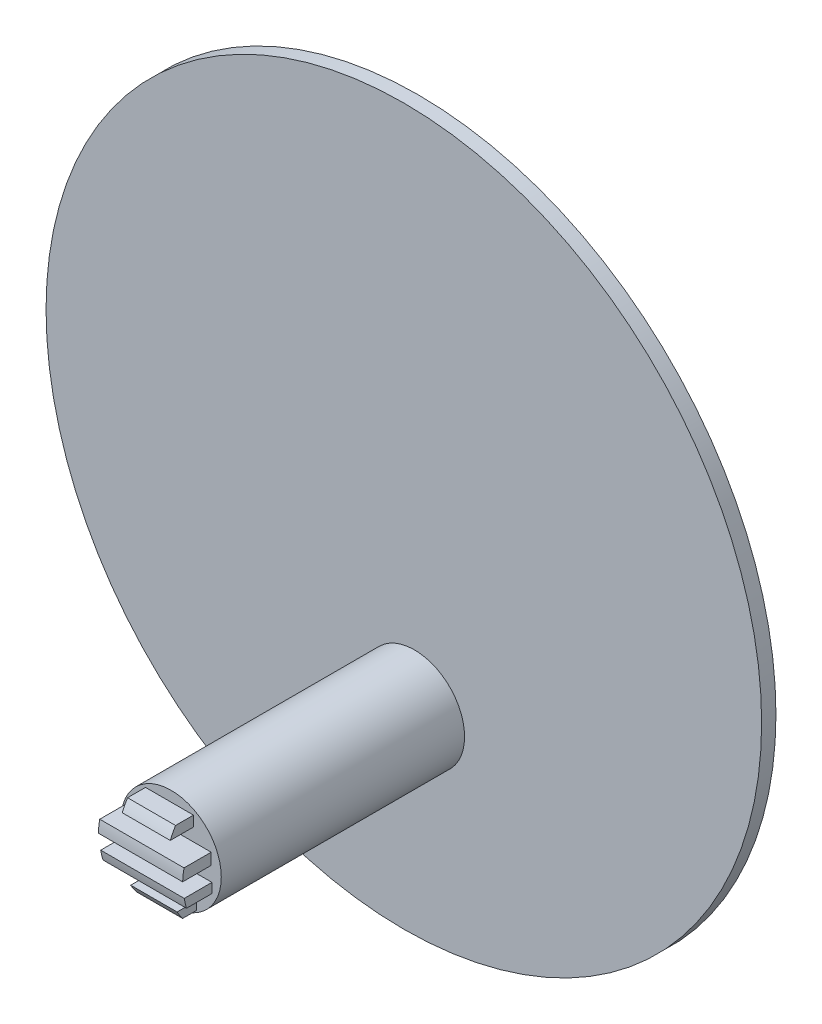
SolidWorks part; units mm, degrees
ref_plane "Front Plane" through (0, 0, 0) normal (0, 0, 1) x (1, 0, 0)
ref_plane "Top Plane" through (0, 0, 0) normal (0, 1, 0) x (1, 0, 0)
ref_plane "Right Plane" through (0, 0, 0) normal (1, 0, 0) x (0, 0, -1)
sketch "Sketch1" plane through (0, 0, 0) normal (0, 0, 1) x (1, 0, 0)
  circle A0 centre (-6.1844, 0) radius 10
  dimension "D1" = 20
extrude "Boss-Extrude1" add sketch "Sketch1" along normal blind 0.4
sketch "Sketch2" plane through (0, 0, 0.4) normal (0, 0, 1) x (1, 0, 0)
  circle A0 centre (-5.8869, -4.4881) radius 1.4
  dimension "D1" = 2.8
extrude "Boss-Extrude2" add sketch "Sketch2" along normal blind 6.8
sketch "Sketch5" plane through (0, 0, 7.2) normal (0, 0, 1) x (1, 0, 0)
  line L1 (-6.474, -5.6393) -> (-5.1772, -5.6393)
  line L2 (-6.474, -5.6393) -> (-6.474, -5.405)
  line L3 (-6.474, -5.405) -> (-5.1772, -5.405)
  line L4 (-5.1772, -5.6393) -> (-5.1772, -5.405)
extrude "Boss-Extrude4" add sketch "Sketch5" along normal up to surface (0.3908 mm away) separate body
sketch "Sketch6" plane through (0, 0, 7.2) normal (0, 0, 1) x (1, 0, 0)
  line L1 (-7.0819, -5.0165) -> (-4.7474, -5.0165)
  line L2 (-7.0819, -5.0165) -> (-7.0819, -4.7462)
  line L3 (-7.0819, -4.7462) -> (-4.7474, -4.7462)
  line L4 (-4.7474, -5.0165) -> (-4.7474, -4.7462)
extrude "Boss-Extrude5" add sketch "Sketch6" along normal up to surface (0.7112 mm away)
sketch "Sketch7" plane through (0, 0, 7.2) normal (0, 0, 1) x (1, 0, 0)
  line L1 (-7.1245, -4.3448) -> (-4.7686, -4.3448)
  line L2 (-7.1245, -4.3448) -> (-7.1245, -4.0262)
  line L3 (-7.1245, -4.0262) -> (-4.7686, -4.0262)
  line L4 (-4.7686, -4.3448) -> (-4.7686, -4.0262)
extrude "Boss-Extrude6" add sketch "Sketch7" along normal up to surface (0.7983 mm away)
sketch "Sketch8" plane through (0, 0, 7.2) normal (0, 0, 1) x (1, 0, 0)
  line L1 (-6.605, -3.6651) -> (-5.2636, -3.6651)
  line L2 (-6.605, -3.6651) -> (-6.605, -3.3759)
  line L3 (-6.605, -3.3759) -> (-5.2636, -3.3759)
  line L4 (-5.2636, -3.6651) -> (-5.2636, -3.3759)
extrude "Boss-Extrude7" add sketch "Sketch8" along normal up to surface (0.6491 mm away)
